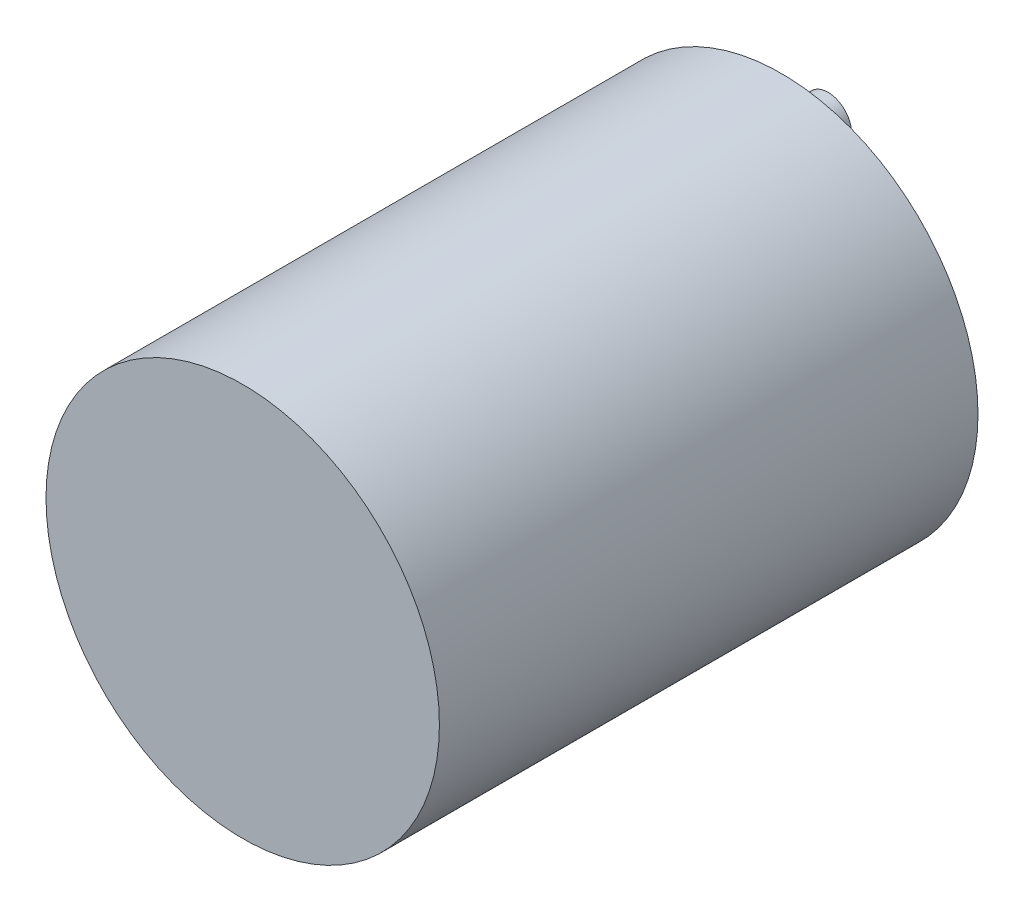
SolidWorks part; units mm, degrees
ref_plane "Front Plane" through (0, 0, 0) normal (0, 0, 1) x (1, 0, 0)
ref_plane "Top Plane" through (0, 0, 0) normal (0, 1, 0) x (1, 0, 0)
ref_plane "Right Plane" through (0, 0, 0) normal (1, 0, 0) x (0, 0, -1)
sketch "Sketch1" plane through (0, 0, 0) normal (0, 0, 1) x (1, 0, 0)
  circle A0 centre (0, 0) radius 21
  dimension "D1" = 42
extrude "Boss-Extrude1" add sketch "Sketch1" along normal blind 57.5
sketch "Sketch2" plane through (0, 0, 0) normal (0, 0, 1) x (1, 0, 0)
  line L0 (0, 0) -> (0, 26.9084) construction
  circle A0 centre (0, 14.25) radius 2.5
  circle A1 centre (12.3409, -7.125) radius 2.5
  circle A2 centre (-12.3409, -7.125) radius 2.5
  point P3 (0, 14.25)
  point P12 (0, 0)
  dimension "D2" = 5
  dimension "D1" = 14.25
  dimension "D3" = 3
extrude "Boss-Extrude2" add sketch "Sketch2" against normal blind 5
